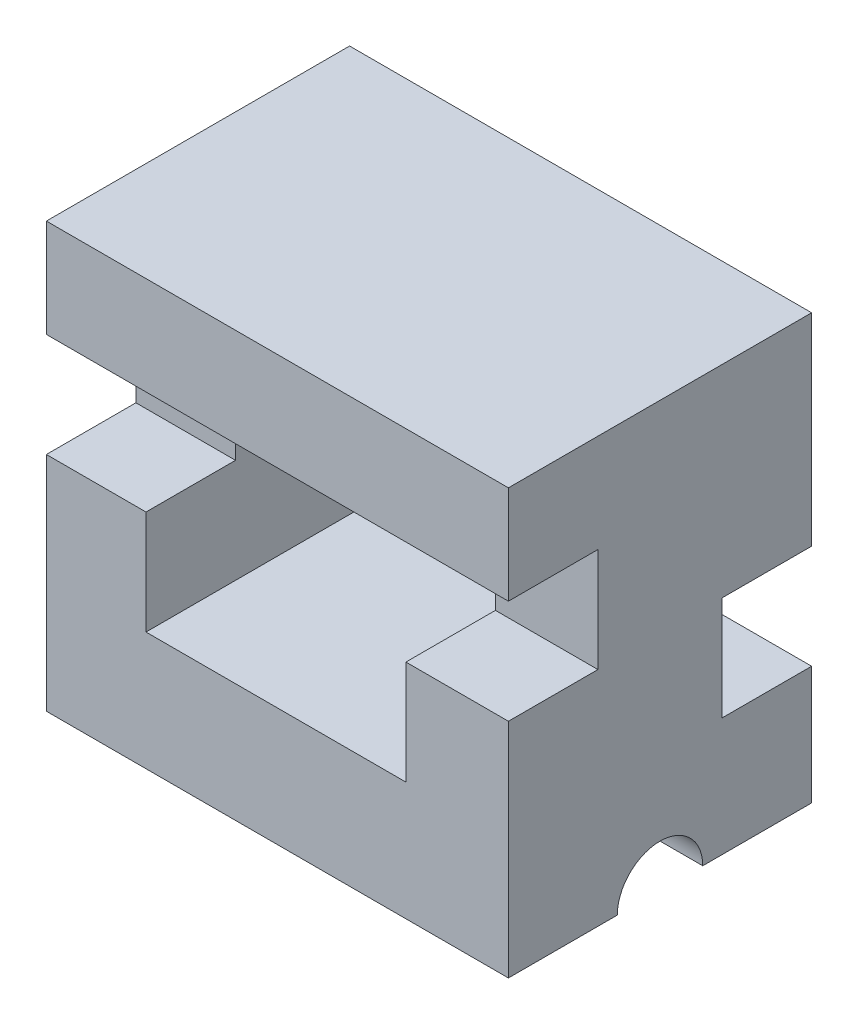
SolidWorks part; units mm, degrees
material "1.3# EPP"
ref_plane "Front Plane" through (0, 0, 0) normal (0, 0, 1) x (1, 0, 0)
ref_plane "Top Plane" through (0, 0, 0) normal (0, 1, 0) x (1, 0, 0)
ref_plane "Right Plane" through (0, 0, 0) normal (1, 0, 0) x (0, 0, -1)
sketch "Sketch2" plane through (0, 0, 0) normal (0, 1, 0) x (1, 0, 0)
  line L1 (0, 0) -> (40.64, 0)
  line L2 (0, 0) -> (0, 26.67)
  line L3 (0, 26.67) -> (40.64, 26.67)
  line L4 (40.64, 0) -> (40.64, 26.67)
  dimension "D1" = 26.67
  dimension "D2" = 40.64
extrude "Boss-Extrude1" add sketch "Sketch2" along normal blind 37.338
sketch "Sketch3" plane through (40.64, 0, 0) normal (1, 0, 0) x (0, 0, -1)
  line L0 (0, 0) -> (26.67, 0) construction
  circle A0 centre (13.335, 0) radius 3.7592
  dimension "D1" = 7.5184
extrude "Body Tube Cut" cut sketch "Sketch3" against normal through all
sketch "Sketch4" plane through (0, 0, 0) normal (0, 0, 1) x (1, 0, 0)
  line L0 (0, 0) -> (40.64, 0) construction
  line L1 (8.763, 28.702) -> (31.623, 28.702)
  line L2 (8.763, 28.702) -> (8.763, 10.414)
  line L3 (8.763, 10.414) -> (31.623, 10.414)
  line L4 (31.623, 28.702) -> (31.623, 10.414)
  line L5 (0, 37.338) -> (0, 0) construction
  dimension "D1" = 18.288
  dimension "D2" = 10.414
  dimension "D3" = 22.86
  dimension "D4" = 8.763
extrude "Servo Body Hole" cut sketch "Sketch4" against normal up to surface (26.67 mm away) up to face at (20.32, 18.669, -26.67)
sketch "Sketch5" plane through (40.64, 0, 0) normal (1, 0, 0) x (0, 0, -1)
  line L0 (26.67, 10.414) -> (0, 10.414) construction
  line L1 (26.67, 10.414) -> (0, 10.414)
  line L2 (26.67, 28.702) -> (0, 28.702) construction
  line L3 (26.67, 28.702) -> (0, 28.702)
  line L5 (0, 28.702) -> (7.874, 28.702)
  line L6 (0, 28.702) -> (0, 19.558)
  line L7 (0, 19.558) -> (7.874, 19.558)
  line L8 (7.874, 28.702) -> (7.874, 19.558)
  line L9 (26.67, 10.414) -> (18.796, 10.414)
  line L10 (26.67, 10.414) -> (26.67, 19.558)
  line L11 (26.67, 19.558) -> (18.796, 19.558)
  line L12 (18.796, 10.414) -> (18.796, 19.558)
  line M4 (26.67, 0) -> (26.67, 37.338)
  line M6 (0, 37.338) -> (0, 0)
  dimension "D1" = 9.144
  dimension "D2" = 7.874
  dimension "D3" = 7.874
  dimension "D4" = 9.144
extrude "Cut-Extrude3" cut sketch "Sketch5" against normal up to surface (40.64 mm away) contours L8 L3 L7 M6 | L12 L1 L11 M4 up to face at (0, 13.0725, -13.335)
